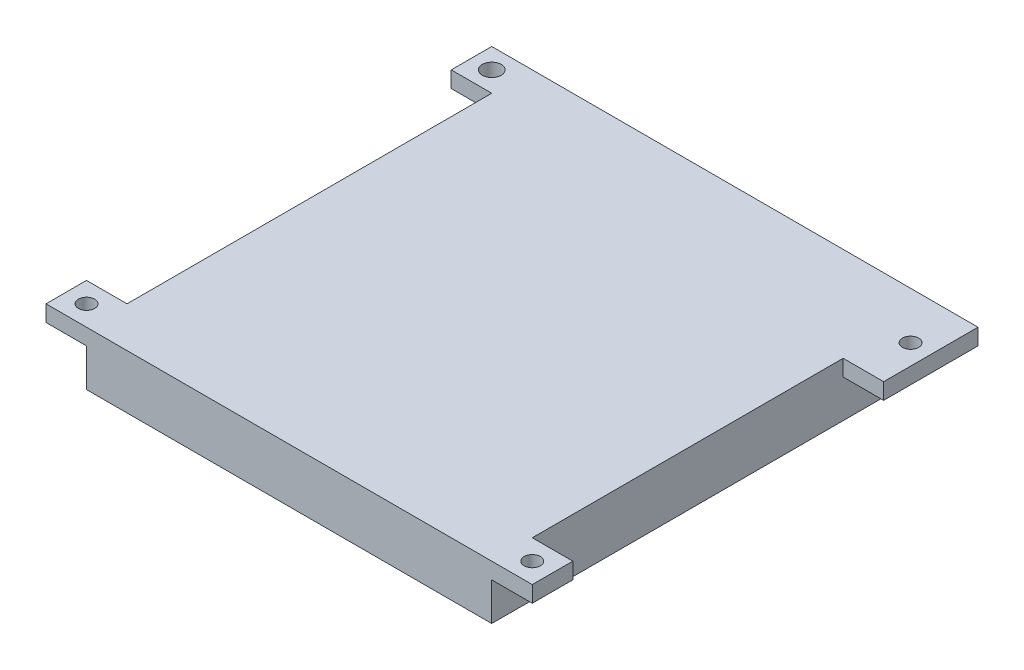
SolidWorks part; units mm, degrees
ref_plane "Спереди" through (0, 0, 0) normal (0, 0, 1) x (1, 0, 0)
ref_plane "Сверху" through (0, 0, 0) normal (0, 1, 0) x (1, 0, 0)
ref_plane "Справа" through (0, 0, 0) normal (1, 0, 0) x (0, 0, -1)
sketch "Эскиз1" plane through (0, 0, 0) normal (0, 1, 0) x (1, 0, 0)
  line L0 (124.9998, -51.9331) -> (124.9998, -51.9334)
  line L3 (49.9998, -131.9701) -> (199.9998, -131.9701)
  line L4 (49.9998, -131.9701) -> (49.9998, 33.0299)
  line L5 (49.9998, 33.0299) -> (199.9998, 33.0299)
  line L6 (199.9998, -131.9701) -> (199.9998, 33.0299)
  line L7 (49.9998, -131.9701) -> (199.9998, 33.0299) construction
  line L8 (49.9998, 33.0299) -> (199.9998, -131.9701) construction
  point P2 (0, 0)
  point P5 (124.9998, -49.4701)
  dimension "D1" = 150
  dimension "D2" = 165
extrude "Бобышка-Вытянуть1" add sketch "Эскиз1" against normal blind 20
sketch "Эскиз2" plane through (0, 0, 0) normal (0, 1, 0) x (1, 0, 0)
  line L0 (34.9998, 33.0299) -> (49.9998, 18.0299) construction
  line L1 (49.9998, 33.0299) -> (34.9998, 33.0299)
  line L2 (49.9998, 33.0299) -> (49.9998, 18.0299)
  line L3 (49.9998, 18.0299) -> (34.9998, 18.0299)
  line L4 (34.9998, 33.0299) -> (34.9998, 18.0299)
  line L5 (49.9998, 33.0299) -> (34.9998, 18.0299) construction
  line L6 (214.9998, 33.0299) -> (199.9998, -1.8965) construction
  line L7 (199.9998, 33.0299) -> (214.9998, 33.0299)
  line L8 (199.9998, 33.0299) -> (199.9998, -1.8965)
  line L9 (199.9998, -1.8965) -> (214.9998, -1.8965)
  line L10 (214.9998, 33.0299) -> (214.9998, -1.8965)
  line L11 (199.9998, 33.0299) -> (214.9998, -1.8965) construction
  line L12 (214.9998, -116.9701) -> (199.9998, -131.9701) construction
  line L13 (199.9998, -131.9701) -> (214.9998, -131.9701)
  line L14 (199.9998, -131.9701) -> (199.9998, -116.9701)
  line L15 (199.9998, -116.9701) -> (214.9998, -116.9701)
  line L16 (214.9998, -131.9701) -> (214.9998, -116.9701)
  line L17 (199.9998, -116.9701) -> (214.9998, -131.9701) construction
  line L18 (49.9998, -116.9701) -> (34.9998, -131.9701) construction
  line L19 (49.9998, -131.9701) -> (34.9998, -131.9701)
  line L20 (49.9998, -131.9701) -> (49.9998, -116.9701)
  line L21 (49.9998, -116.9701) -> (34.9998, -116.9701)
  line L22 (34.9998, -131.9701) -> (34.9998, -116.9701)
  line L23 (34.9998, -116.9701) -> (49.9998, -131.9701) construction
  circle A0 centre (42.4998, 25.5299) radius 3.5
  circle A1 centre (207.4998, 15.5667) radius 3
  circle A2 centre (207.4998, -124.4701) radius 3
  circle A3 centre (42.4998, -124.4701) radius 3
extrude "Бобышка-Вытянуть2" add sketch "Эскиз2" against normal blind 6
sketch "Эскиз4" plane through (0, -20, 0) normal (0, -1, 0) x (1, 0, 0)
  line L0 (49.9998, 131.9701) -> (199.9998, -33.0299) construction
  line L1 (49.9998, -33.0299) -> (199.9998, 131.9701) construction
  line L2 (124.9998, 131.9701) -> (124.9998, -33.0299) construction
  line L3 (49.9998, 131.9701) -> (199.9998, 131.9701) construction
  line L4 (49.9998, -33.0299) -> (199.9998, -33.0299) construction
  line L5 (199.9998, 34.4701) -> (49.9998, 34.4701) construction
  line L6 (199.9998, 131.9701) -> (199.9998, -33.0299) construction
  line L7 (49.9998, 131.9701) -> (49.9998, -33.0299) construction
  line L8 (124.9998, 34.4701) -> (199.9998, 116.9701) construction
  line L10 (163.8366, 77.1905) -> (68.5844, 46.7435)
  line L11 (68.5844, 46.7435) -> (142.5784, -20.5238)
  line L12 (142.5784, -20.5238) -> (163.8366, 77.1905)
  circle A0 centre (124.9998, 34.4701) radius 28.8675 construction
  circle A1 centre (163.8366, 77.1905) radius 3
  circle A2 centre (142.5784, -20.5238) radius 3
  circle A3 centre (68.5844, 46.7435) radius 3
  point P20 (124.9998, 49.4701)
  point P30 (163.8366, 77.1905)
  dimension "D1" = 15
  dimension "D2" = 100
extrude "Вырез-Вытянуть1" cut sketch "Эскиз4" against normal blind 15 contours A1 | A2 | A3
